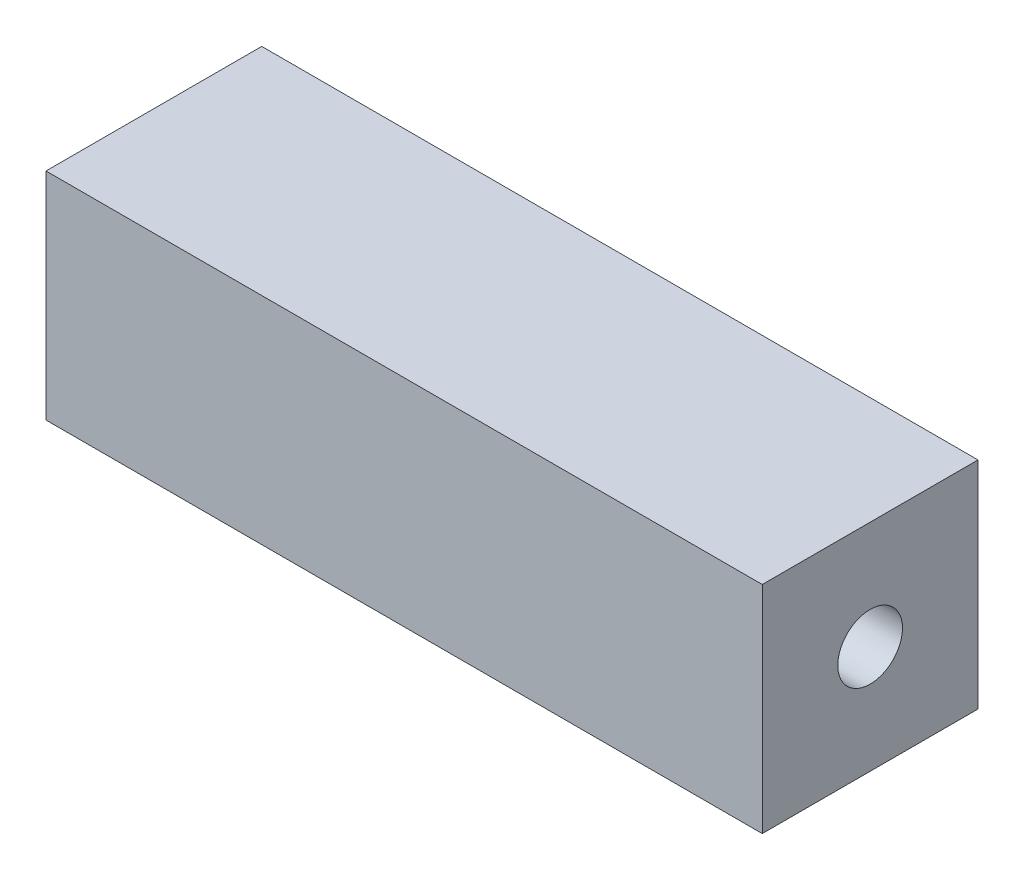
SolidWorks part; units mm, degrees
ref_plane "正面" through (0, 0, 0) normal (0, 0, 1) x (1, 0, 0)
ref_plane "平面" through (0, 0, 0) normal (0, 1, 0) x (1, 0, 0)
ref_plane "右側面" through (0, 0, 0) normal (1, 0, 0) x (0, 0, -1)
sketch "ｽｹｯﾁ2" plane through (0, 0, 0) normal (0, 1, 0) x (1, 0, 0)
  line L1 (-16.6, -5) -> (16.6, -5)
  line L2 (-16.6, -5) -> (-16.6, 5)
  line L3 (-16.6, 5) -> (16.6, 5)
  line L4 (16.6, -5) -> (16.6, 5)
  line L5 (-16.6, -5) -> (16.6, 5) construction
  line L6 (-16.6, 5) -> (16.6, -5) construction
  point P0 (0, 0)
  dimension "D1" = 10
  dimension "D2" = 33.2
extrude "ﾎﾞｽ - 押し出し1" add sketch "ｽｹｯﾁ2" along normal mid plane 10
sketch "ｽｹｯﾁ3" plane through (0, 0, 0) normal (1, 0, 0) x (0, 0, -1)
  circle A0 centre (0, 0) radius 1.5
  dimension "D1" = 3
extrude "ｶｯﾄ - 押し出し1" cut sketch "ｽｹｯﾁ3" against normal through all both and the other way through all
